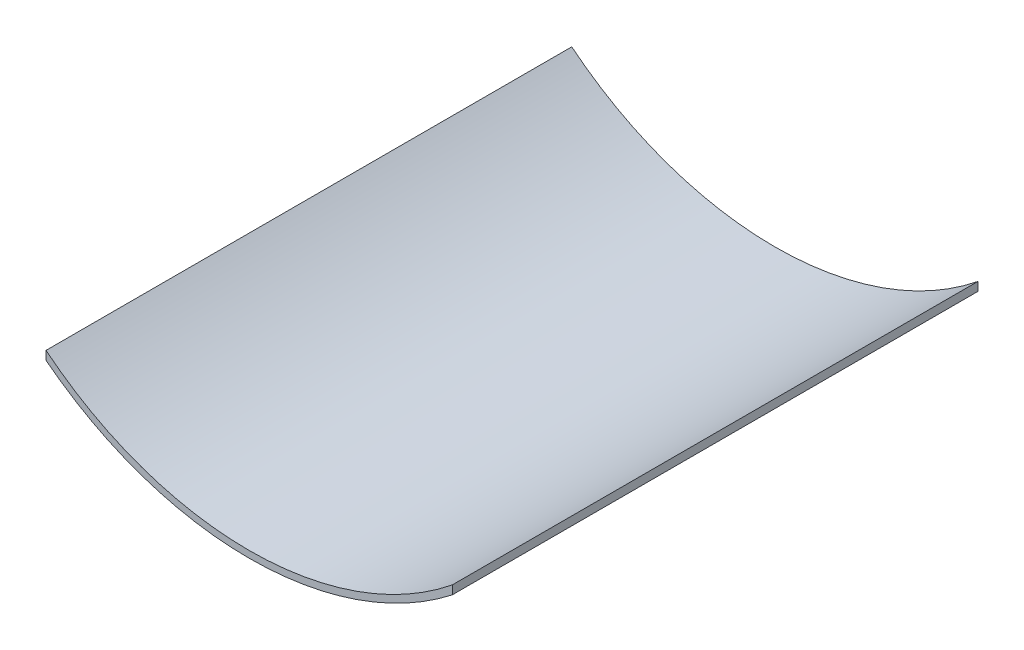
SolidWorks part; units mm, degrees
ref_plane "Front Plane" through (0, 0, 0) normal (0, 0, 1) x (1, 0, 0)
ref_plane "Top Plane" through (0, 0, 0) normal (0, 1, 0) x (1, 0, 0)
ref_plane "Right Plane" through (0, 0, 0) normal (1, 0, 0) x (0, 0, -1)
sketch "Sketch1" plane through (0, 0, 0) normal (0, 0, 1) x (1, 0, 0)
  line L0 (-206.4011, 77.8555) -> (-206.4011, 70.6185)
  line L1 (133.5989, 77.8555) -> (133.5989, 70.6185)
  arc A0 (-206.4011, 70.6185) -> (133.5989, 70.6185) centre (-36.4011, 288.6889) ccw
  arc A1 (-206.4011, 77.8555) -> (133.5989, 77.8555) centre (-36.4011, 288.6889) ccw
extrude "Boss-Extrude1" add sketch "Sketch1" along normal blind 440
